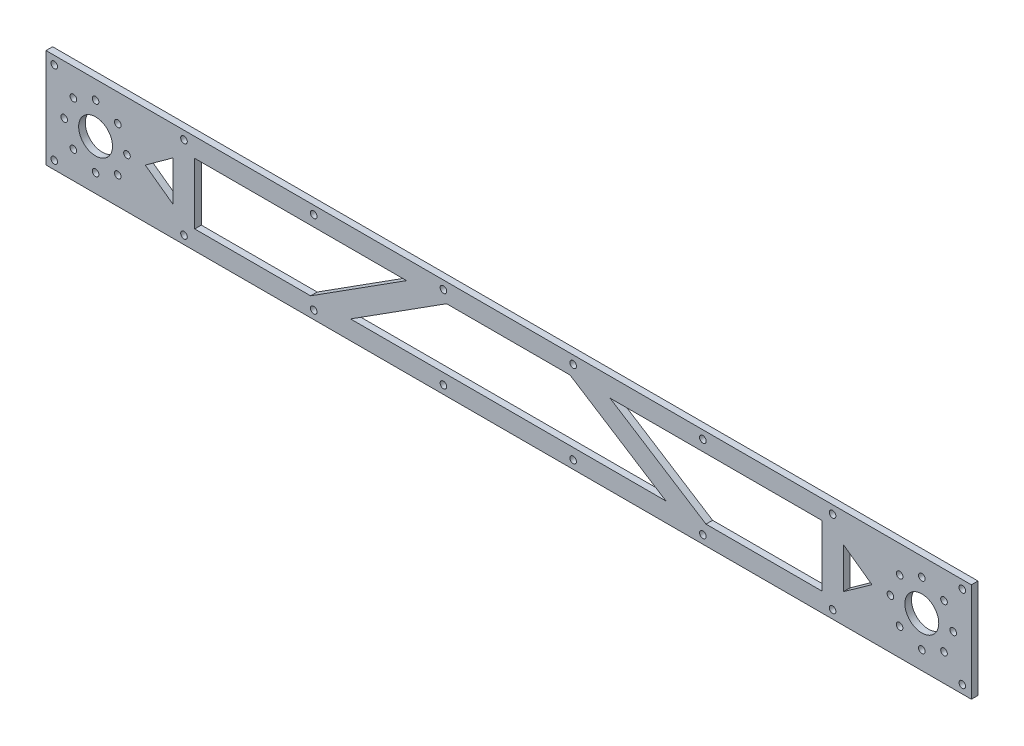
SolidWorks part; units mm, degrees
ref_plane "前视基准面" through (0, 0, 0) normal (0, 0, 1) x (1, 0, 0)
ref_plane "上视基准面" through (0, 0, 0) normal (0, 1, 0) x (1, 0, 0)
ref_plane "右视基准面" through (0, 0, 0) normal (1, 0, 0) x (0, 0, -1)
sketch "草图1" plane through (0, 0, 0) normal (0, 0, 1) x (1, 0, 0)
  line L0 (0, 0) -> (480, 0) construction
  line L1 (480, 0) -> (480, 20) construction
  line L2 (480, 0) -> (500, 0) construction
  line L3 (500, 0) -> (500, 30) construction
  line L4 (-30, 30) -> (530, 30)
  line L5 (-30, 30) -> (-30, -30)
  line L6 (-30, -30) -> (530, -30)
  line L7 (530, 30) -> (530, -30)
  line L8 (500, 0) -> (500, -30) construction
  line L9 (500, 0) -> (530, 0) construction
  line L10 (0, 0) -> (-30, 0) construction
  circle A0 centre (0, 0) radius 10.25
  circle A2 centre (0, 0) radius 19 construction
  circle A3 centre (0, -19) radius 2
  circle A4 centre (-13.435, -13.435) radius 2
  circle A5 centre (-19, 0) radius 2
  circle A6 centre (-13.435, 13.435) radius 2
  circle A7 centre (0, 19) radius 2
  circle A8 centre (13.435, 13.435) radius 2
  circle A9 centre (19, 0) radius 2
  circle A10 centre (13.435, -13.435) radius 2
  circle A12 centre (500, 0) radius 2 construction
  circle A17 centre (500, 0) radius 19 construction
  circle A18 centre (500, -19) radius 2
  circle A26 centre (500, 0) radius 10.25
  circle A34 centre (486.565, -13.435) radius 2
  circle A35 centre (481, 0) radius 2
  circle A36 centre (486.565, 13.435) radius 2
  circle A37 centre (500, 19) radius 2
  circle A38 centre (513.435, 13.435) radius 2
  circle A39 centre (519, 0) radius 2
  circle A40 centre (513.435, -13.435) radius 2
  dimension "D1" = 38
  dimension "D2" = 8
  dimension "D3" = 20.5
  dimension "D4" = 500
  dimension "D5" = 4
  dimension "D11" = 4
  dimension "D6" = 20
  dimension "D7" = 20
  dimension "D9" = 30
  dimension "D10" = 30
  dimension "D8" = 8
extrude "凸台-拉伸1" add sketch "草图1" along normal blind 4
sketch "草图2" plane through (0, 0, 4) normal (0, 0, 1) x (1, 0, 0)
  line L0 (-25, 25) -> (-25, 30) construction
  line L1 (530, 30) -> (-30, 30) construction
  line L2 (-25, 25) -> (-30, 25) construction
  line L3 (-30, 30) -> (-30, -30) construction
  line L4 (0, 0) -> (54.3879, 0) construction
  circle A0 centre (-25, 25) radius 2
  circle A1 centre (53.5, 25) radius 2
  circle A2 centre (132, 25) radius 2
  circle A3 centre (210.5, 25) radius 2
  circle A4 centre (289, 25) radius 2
  circle A5 centre (367.5, 25) radius 2
  circle A6 centre (446, 25) radius 2
  circle A7 centre (524.5, 25) radius 2
  circle A8 centre (53.5, -25) radius 2
  circle A9 centre (132, -25) radius 2
  circle A10 centre (210.5, -25) radius 2
  circle A11 centre (289, -25) radius 2
  circle A12 centre (367.5, -25) radius 2
  circle A13 centre (446, -25) radius 2
  circle A14 centre (524.5, -25) radius 2
  circle A15 centre (-25, -25) radius 2
  dimension "D1" = 8
  dimension "D2" = 2
extrude "切除-拉伸1" cut sketch "草图2" against normal blind 10
sketch "草图3" plane through (0, 0, 4) normal (0, 0, 1) x (1, 0, 0)
  line L0 (53.5, 25) -> (210.5, 25) construction
  line L1 (210.5, 25) -> (132, -25)
  line L2 (132, -25) -> (53.5, -25) construction
  line L3 (53.5, -25) -> (53.5, 25) construction
  line L4 (210.5, 25) -> (289, 25) construction
  line L5 (289, 25) -> (367.5, -25) construction
  line L6 (367.5, -25) -> (132, -25) construction
  line L7 (367.5, -25) -> (446, -25) construction
  line L8 (446, -25) -> (446, 25) construction
  line L9 (446, 25) -> (289, 25) construction
  line L10 (60, 18.5) -> (188.1957, 18.5)
  line L11 (188.1957, 18.5) -> (130.1057, -18.5)
  line L12 (130.1057, -18.5) -> (60, -18.5)
  line L13 (60, -18.5) -> (60, 18.5)
  line L14 (212.3943, 18.5) -> (287.1057, 18.5)
  line L15 (287.1057, 18.5) -> (345.1957, -18.5)
  line L16 (345.1957, -18.5) -> (154.3043, -18.5)
  line L17 (212.3943, 18.5) -> (154.3043, -18.5)
  line L18 (439.5, 18.5) -> (311.3043, 18.5)
  line L19 (311.3043, 18.5) -> (369.3943, -18.5)
  line L20 (369.3943, -18.5) -> (439.5, -18.5)
  line L21 (439.5, -18.5) -> (439.5, 18.5)
  line L22 (19, 0) -> (53.5, 25) construction
  line L23 (53.5, -25) -> (19, 0) construction
  line L24 (47, -12.2627) -> (30.0775, 0)
  line L25 (30.0775, 0) -> (47, 12.2627)
  line L26 (47, -12.2627) -> (47, 12.2627)
  line L27 (446, 25) -> (481, 0) construction
  line L28 (481, 0) -> (446, -25) construction
  line L29 (452.5, 12.3693) -> (469.817, 0)
  line L30 (469.817, 0) -> (452.5, -12.3693)
  line L31 (452.5, -12.3693) -> (452.5, 12.3693)
  dimension "D1" = 6.5
  dimension "D2" = 6.5
  dimension "D3" = 6.5
  dimension "D4" = 6.5
  dimension "D5" = 6.5
extrude "切除-拉伸2" cut sketch "草图3" against normal blind 10 contours L13 L12 L11 L10 | L14 L17 L16 L15 | L20 L21 L18 L19 | L31 L30 L29 | L24 L26 L25
